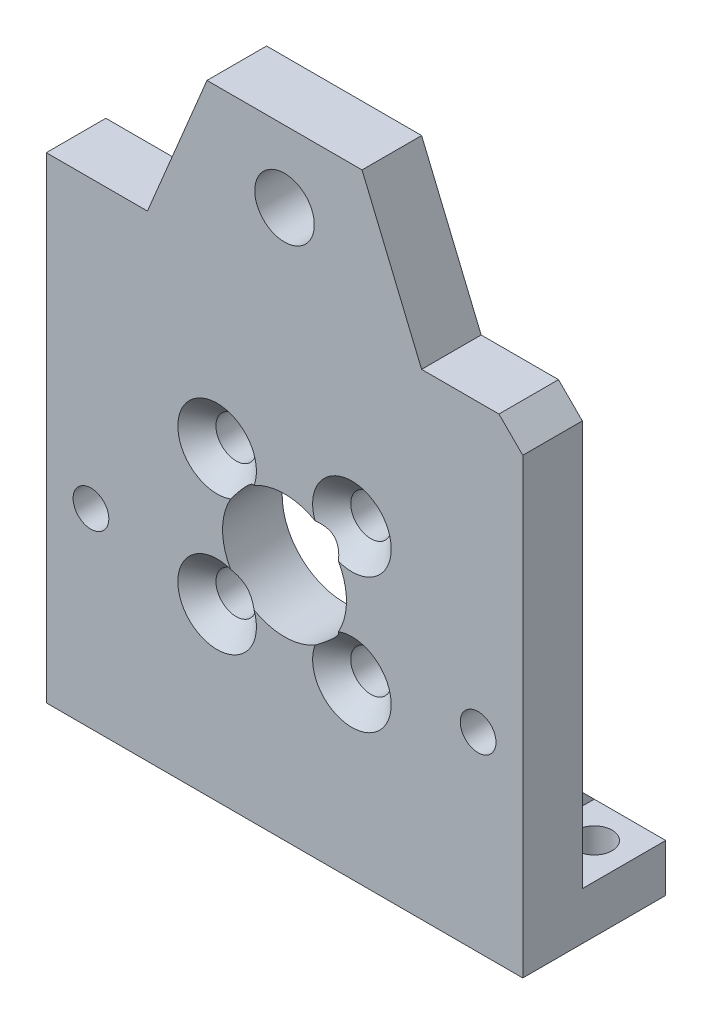
SolidWorks part; units mm, degrees
ref_plane "前视基准面" through (0, 0, 0) normal (0, 0, 1) x (1, 0, 0)
ref_plane "上视基准面" through (0, 0, 0) normal (0, 1, 0) x (1, 0, 0)
ref_plane "右视基准面" through (0, 0, 0) normal (1, 0, 0) x (0, 0, -1)
other "Configuration Table"
sketch "草图1" plane through (0, 0, 0) normal (0, 0, 1) x (1, 0, 0)
  line L0 (-20, 0) -> (20, 0) construction
  line L1 (-20, -20) -> (20, -20)
  line L2 (-20, -20) -> (-20, 20)
  line L3 (-20, 20) -> (20, 20)
  line L4 (20, -20) -> (20, 20)
  line L5 (-20, -20) -> (20, 20) construction
  line L6 (-20, 20) -> (20, -20) construction
  line L7 (0, 20) -> (0, -20) construction
  line L9 (-5.6569, -5.6569) -> (5.6569, -5.6569) construction
  line L10 (-5.6569, -5.6569) -> (-5.6569, 5.6569) construction
  line L11 (-5.6569, 5.6569) -> (5.6569, 5.6569) construction
  line L12 (5.6569, -5.6569) -> (5.6569, 5.6569) construction
  line L13 (-5.6569, -5.6569) -> (5.6569, 5.6569) construction
  line L14 (-5.6569, 5.6569) -> (5.6569, -5.6569) construction
  circle A2 centre (0, 0) radius 5.2
  circle A3 centre (0, 0) radius 8 construction
  circle A4 centre (5.6569, 5.6569) radius 1.6
  circle A5 centre (5.6569, -5.6569) radius 1.6
  circle A6 centre (-5.6569, -5.6569) radius 1.6
  circle A7 centre (-5.6569, 5.6569) radius 1.6
  point P0 (0, 0)
  point P31 (0, 0)
  dimension "D6" = 10.4
  dimension "D7" = 16
  dimension "D8" = 3.2
  dimension "D1" = 40
  dimension "D2" = 40
  dimension "D9" = 4
extrude "凸台-拉伸1" add sketch "草图1" along normal blind 5
hole_wizard "孔1" positions "3D草图1" profile "草图2" legacy end condition through all
sketch3d "3D草图1"
  line L0 (0, 20, 5) -> (0, -20, 5) construction
  line L1 (20, 20, 5) -> (-20, 20, 5) construction
  line L2 (-20, -20, 5) -> (20, -20, 5) construction
  line L3 (-20, 0, 5) -> (20, 0, 5) construction
  line L4 (-20, 20, 5) -> (-20, -20, 5) construction
  line L5 (20, -20, 5) -> (20, 20, 5) construction
  point P0 (16.25, -4, 5)
  point P2 (-16.25, -4, 5)
  dimension "D1" = 16.25
  dimension "D2" = 16.25
  dimension "D3" = 4
  dimension "D4" = 4
sketch "草图2" plane through (16.25, -4, 5) normal (1, 0, 0) x (0, -1, 0)
  line L0 (0, 0) -> (0, 5)
  line L1 (0, 5) -> (1.5, 5)
  line L2 (1.5, 5) -> (1.5, 0)
  line L3 (1.5, 0) -> (0, 0)
  line L4 (0, 110) -> (0, -10) construction
  dimension "直径" = 3
  dimension "深度" = 5
chamfer "倒角1" distance 2 angle 45 1 edges at (20, 20, 2.5)
hole_wizard "M3 十字槽沉头木螺钉的锥形沉头孔2" positions "草图5" profile "草图6" countersink size "M3" standard "GB" end condition through all
sketch "草图5" plane through (0, 0, 5) normal (0, 0, 1) x (1, 0, 0)
  point P0 (-5.6569, 5.6569)
  point P3 (5.6569, 5.6569)
  point P6 (5.6569, -5.6569)
  point P9 (-5.6569, -5.6569)
sketch "草图6" plane through (-5.6569, 5.6569, 5) normal (1, 0, 0) x (0, -1, 0)
  line L0 (0, 0) -> (0, 5)
  line L1 (0, 5) -> (1.7, 5)
  line L2 (1.7, 5) -> (1.7, 1.6)
  line L3 (1.7, 1.6) -> (3.3, 0)
  line L5 (3.3, 0) -> (0, 0)
  line L6 (-1.7, 1.6) -> (-3.3, 0) construction
  line L11 (0, -6.35) -> (0, 107.95) construction
  dimension "通孔孔直径" = 3.4
  dimension "通孔孔深度" = 5
  dimension "近端锥形沉头孔直径" = 6.6
  dimension "近端锥形沉头孔角度" = 90
sketch "草图7" plane through (0, 0, 0) normal (0, 0, -1) x (-1, 0, 0)
  line L0 (0, -20) -> (0, 33.662) construction
  line L1 (20, -20) -> (-20, -20) construction
  line L2 (-18, 20) -> (20, 20) construction
  line L3 (-6.5078, 20) -> (6.5078, 20)
  line L4 (-6.5078, 20) -> (-6.5078, 32) construction
  line L5 (-6.5078, 32) -> (6.5078, 32)
  line L6 (6.5078, 20) -> (6.5078, 32) construction
  line L7 (6.5078, 32) -> (11.5078, 20)
  line L8 (-6.5078, 32) -> (-11.5078, 20)
  line L9 (-6.5078, 26) -> (6.5078, 26) construction
  circle A1 centre (0, 26) radius 2.5
  point P17 (0, 0)
  line M11 (20, 20) -> (-18, 20)
  dimension "D4" = 5
  dimension "D1" = 5
  dimension "D2" = 5
  dimension "D3" = 12
extrude "凸台-拉伸2" add sketch "草图7" against normal up to surface (5 mm away) contours L5 L8 L7 A1 M11 up to face at (17.75, -4, 5)
sketch "草图10" plane through (0, -20, 0) normal (0, -1, 0) x (1, 0, 0)
  line L1 (20, 0) -> (11, 0)
  line L2 (20, 0) -> (20, -7)
  line L3 (20, -7) -> (11, -7)
  line L4 (11, 0) -> (11, -7)
  circle A0 centre (17, -4) radius 1.5
  dimension "D5" = 3
  dimension "D1" = 7
  dimension "D2" = 9
  dimension "D3" = 4
  dimension "D4" = 3
extrude "凸台-拉伸4" add sketch "草图10" against normal blind 4
ref_plane "基准面1" through (0, 0, 0) normal (1, 0, 0) x (0, 0, -1)
sketch "草图12" plane through (11, 0, 0) normal (-1, 0, 0) x (0, 0, 1)
  line L0 (-7, -16) -> (0, -9)
  line L1 (0, 20) -> (0, -20) construction
  line L2 (0, -9) -> (0, -16)
  line L3 (0, -16) -> (-7, -16)
  dimension "D1" = 45
extrude "凸台-拉伸6" add sketch "草图12" against normal blind 3
mirror "镜向2" about plane through (0, 0, 0) normal (1, 0, 0) of "凸台-拉伸4", "凸台-拉伸6"
